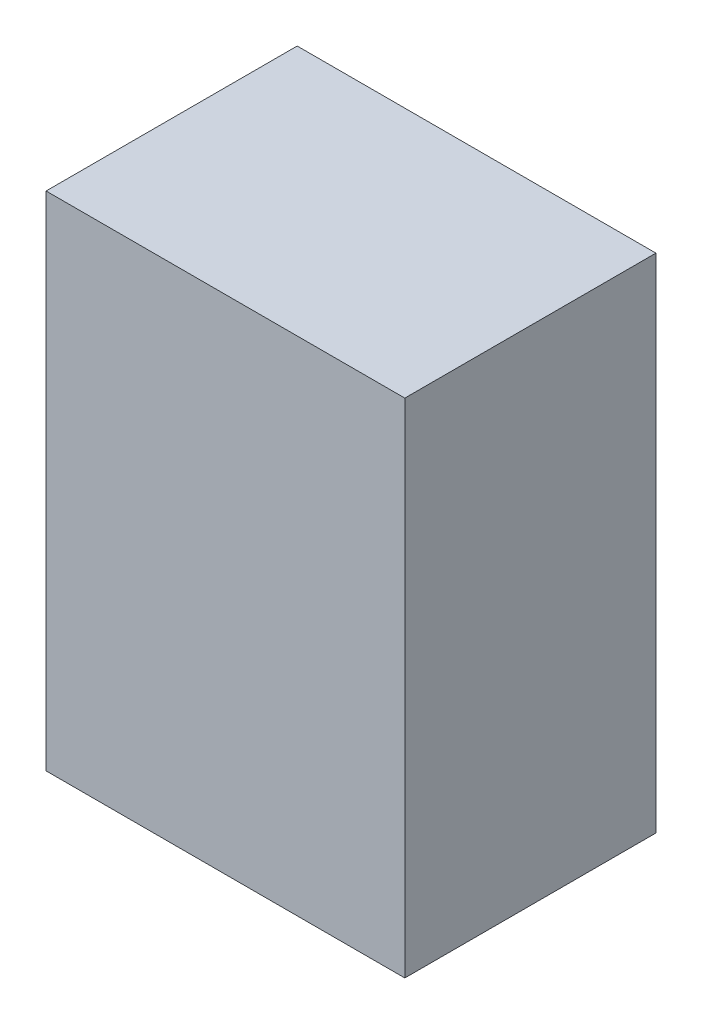
SolidWorks part; units mm, degrees
ref_plane "Front Plane" through (0, 0, 0) normal (0, 0, 1) x (1, 0, 0)
ref_plane "Top Plane" through (0, 0, 0) normal (0, 1, 0) x (1, 0, 0)
ref_plane "Right Plane" through (0, 0, 0) normal (1, 0, 0) x (0, 0, -1)
sketch "Sketch1" plane through (0, 0, 0) normal (0, 0, 1) x (1, 0, 0)
  line L1 (0, 0) -> (10, 0)
  line L2 (0, 0) -> (0, 14)
  line L3 (0, 14) -> (10, 14)
  line L4 (10, 0) -> (10, 14)
  dimension "D1" = 10
  dimension "D2" = 14
extrude "Profile" add sketch "Sketch1" along normal blind 7
equation "\"Profile_Depth\"= 7mm"
equation "\"D1@Profile\" = \"Profile_Depth\""
equation "\"Profile_Sketch_1\"= 10mm"
equation "\"D1@Sketch1\" = \"Profile_Sketch_1\""
equation "\"Profile_Sketch_2\"= 14mm"
equation "\"D2@Sketch1\" = \"Profile_Sketch_2\""
equation "\"EnvelopeWidth\"= 10mm"
equation "\"EnvelopeHeight\"= 14mm"
